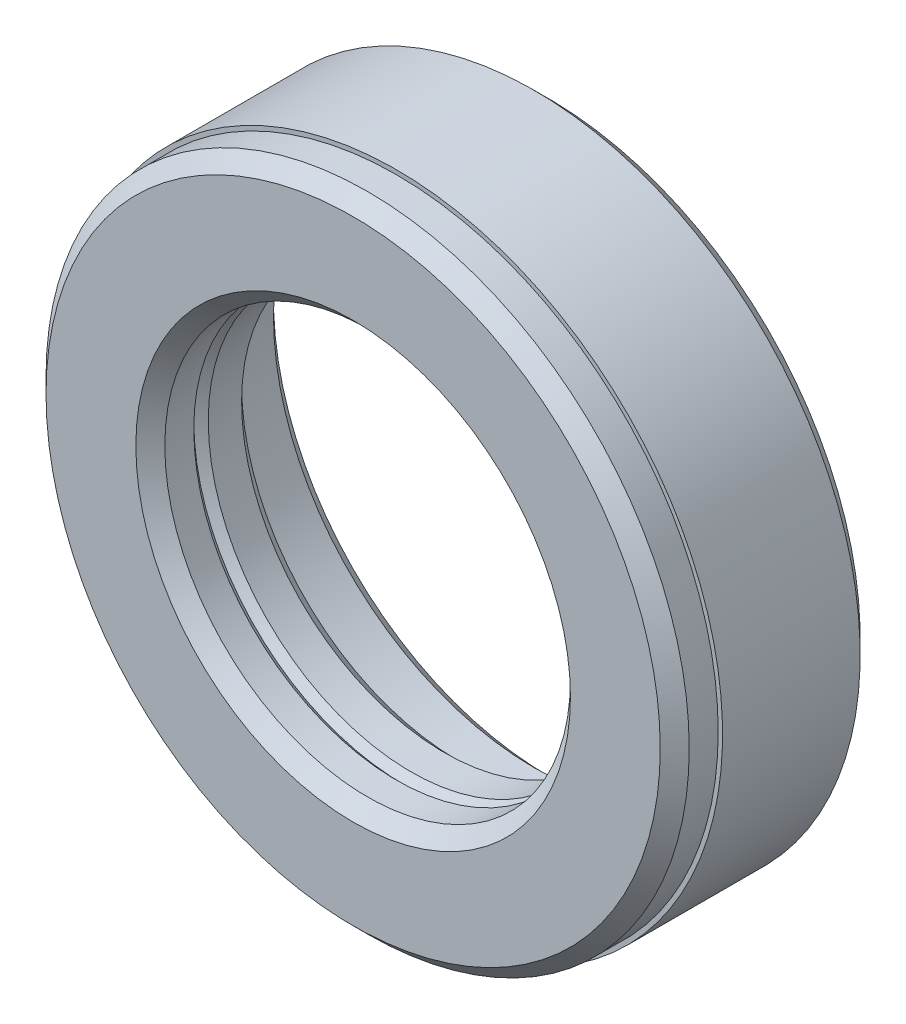
SolidWorks part; units mm, degrees
material "PB01 (C90710) Bronze"
ref_plane "Front Plane" through (0, 0, 0) normal (0, 0, 1) x (1, 0, 0)
ref_plane "Top Plane" through (0, 0, 0) normal (0, 1, 0) x (1, 0, 0)
ref_plane "Right Plane" through (0, 0, 0) normal (1, 0, 0) x (0, 0, -1)
sketch "Sketch1" plane through (0, 0, 0) normal (1, 0, 0) x (0, 0, -1)
  line L0 (0, 0) -> (-13.5, 0)
  line L1 (0, 21.5) -> (0, 0)
  line L2 (-1, 22.5) -> (-10.5, 22.5)
  line L3 (-13.5, 21.2) -> (-13.5, 0)
  line L4 (-13.5, 0) -> (-13.4338, -0.0336)
  line L5 (-10.5, 22.5) -> (-10.5, 22.2)
  line L6 (-10.5, 22.2) -> (-12.5, 22.2)
  line L7 (0, 22.5) -> (-13.5, 22.5) construction
  line L8 (-12.5, 22.2) -> (-13.5, 21.2)
  line L9 (-13.5, 22.5) -> (-13.5, 0) construction
  line L10 (-10.5, 22.5) -> (-10.5, 0) construction
  line L11 (0, 22.2) -> (-13.5, 22.2) construction
  line L12 (0, 21.5) -> (-1, 22.5)
  dimension "D1" = 13.5
  dimension "D2" = 22.5
  dimension "D3" = 22.2
  dimension "D6" = 45
  dimension "D7" = 1
  dimension "D8" = 45
revolve "Revolve1" add sketch "Sketch1" angle 360 about L0
sketch "Sketch2" plane through (0, 0, 0) normal (1, 0, 0) x (0, 0, -1)
  line L0 (0, 0) -> (-13.5, 0)
  line L1 (-13.5, 21.2) -> (-13.5, -21.2) construction
  line L2 (-10, 14.5) -> (-10.5, 14)
  line L3 (-7.2, 14) -> (-9.5, 14)
  line L4 (0, 18) -> (-6.2, 18)
  line L5 (-13.5, 14) -> (-13.5, 0)
  line L6 (0, 18) -> (0, 0)
  line L7 (0, 0) -> (-0.0077, -0.252)
  line L8 (-10.5, 14) -> (-13.5, 14)
  line L9 (-10, 14.5) -> (-10, 12.958) construction
  line L10 (-6.2, 18) -> (-6.2, 15)
  line L11 (-10, 14.5) -> (-9.5, 14)
  line L12 (-6.2, 18) -> (-6.2, 0) construction
  line L13 (0, 14) -> (-13.5, 14) construction
  line L14 (-6.2, 15) -> (-7.2, 14)
  line L15 (0, 18) -> (-13.5, 18) construction
  point P5 (0, 14.5)
  point P6 (-13.5, 14.5)
  point P18 (-6.2, 14)
  dimension "D1" = 13.5
  dimension "D2" = 14
  dimension "D3" = 18
  dimension "D4" = 6.2
  dimension "D5" = 3.5
  dimension "D6" = 90
  dimension "D7" = 14.5
  dimension "D8" = 45
  dimension "D9" = 1
  dimension "D10" = 45
revolve "Cut-Revolve1" cut sketch "Sketch2" angle 360 about L0
chamfer "Chamfer1" distance 1 angle 45 2 edges at (-18, 0, 0) (-14, 0, 13.5)
